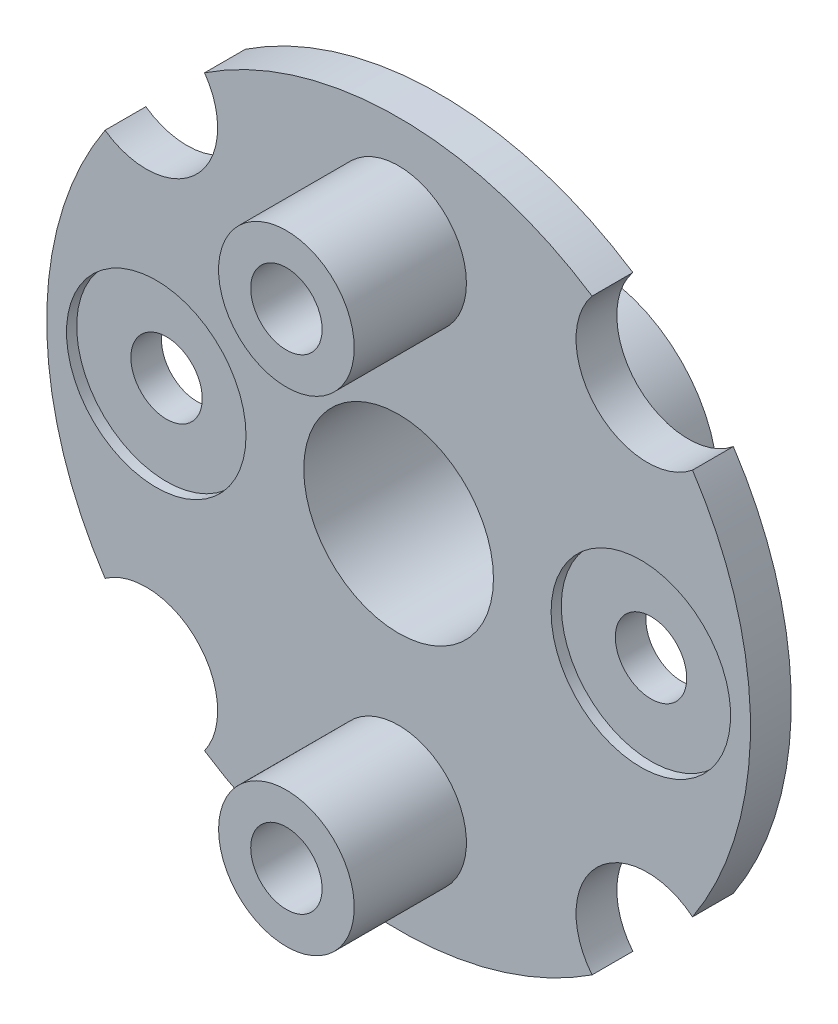
SolidWorks part; units mm, degrees
material "ABS"
ref_plane "Plan de face" through (0, 0, 0) normal (0, 0, 1) x (1, 0, 0)
ref_plane "Plan de dessus" through (0, 0, 0) normal (0, 1, 0) x (1, 0, 0)
ref_plane "Plan de droite" through (0, 0, 0) normal (1, 0, 0) x (0, 0, -1)
sketch "Esquisse1" plane through (0, 0, 0) normal (0, 0, 1) x (1, 0, 0)
  line L0 (0, 0) -> (0, 31.7613) construction
  line L1 (0, 0) -> (40.1621, 0) construction
  line L2 (0, 0) -> (-26.7749, 26.7749) construction
  line L3 (0, 0) -> (27.0466, 27.0466) construction
  arc A0 (-14.3904, 9.5121) -> (-14.3904, -9.5121) centre (0, 0) ccw
  circle A1 centre (0, 0) radius 4.65
  circle A2 centre (0, 11.875) radius 1.75
  circle A3 centre (11.875, 0) radius 1.75
  circle A4 centre (0, 0) radius 11.875 construction
  circle A5 centre (0, -11.875) radius 1.75
  circle A6 centre (-11.875, 0) radius 1.75
  arc A7 (9.4844, 14.4086) -> (14.4086, 9.4844) centre (12.1976, 12.1976) ccw
  arc A8 (-14.3904, 9.5121) -> (-9.5121, 14.3904) centre (-12.3704, 12.3704) ccw
  arc A9 (9.4844, -14.4086) -> (14.4086, -9.4844) centre (12.1976, -12.1976) cw
  arc A10 (-14.3904, -9.5121) -> (-9.5121, -14.3904) centre (-12.3704, -12.3704) cw
  arc A11 (9.4844, 14.4086) -> (-9.5121, 14.3904) centre (0, 0) ccw
  arc A12 (-9.5121, -14.3904) -> (9.4844, -14.4086) centre (0, 0) ccw
  arc A13 (14.4086, -9.4844) -> (12.1976, 12.1976) centre (0, 0) ccw
  dimension "D1" = 34.5
  dimension "D2" = 9.3
  dimension "D3" = 3.5
  dimension "D4" = 23.75
  dimension "D7" = 7
  dimension "D5" = 45
  dimension "D6" = 45
extrude "Boss.-Extru.1" add sketch "Esquisse1" along normal blind 2 contours A9 A13 A7 A11 A8 A0 A10 A12 A6 A1 A2 A3 A5
sketch "Esquisse2" plane through (0, 0, 0) normal (0, 0, -1) x (-1, 0, 0)
  circle A0 centre (0, 0) radius 6.15
  circle A1 centre (0, 0) radius 4.65 construction
  circle A2 centre (0, 0) radius 4.65
extrude "Boss.-Extru.2" add sketch "Esquisse2" along normal blind 7.5
sketch "Esquisse3" plane through (0, 0, 2) normal (0, 0, 1) x (1, 0, 0)
  line L0 (0, 0) -> (30.4064, 0) construction
  circle A0 centre (0, 11.875) radius 3.325
  circle A1 centre (0, 11.875) radius 1.75 construction
  circle A2 centre (0, 11.875) radius 1.75
  circle A3 centre (0, -11.875) radius 1.75
  circle A4 centre (0, -11.875) radius 3.325
  dimension "D1" = 6.65
extrude "Boss.-Extru.3" add sketch "Esquisse3" along normal blind 5.5
sketch "Esquisse4" plane through (0, 0, 2) normal (0, 0, 1) x (1, 0, 0)
  line L0 (0, 0) -> (0, 18.4171) construction
  circle A0 centre (-11.88, 0) radius 4.4
  circle A1 centre (11.875, 0) radius 4.4
  dimension "D1" = 8.8
  dimension "D2" = 11.875
  dimension "D3" = 11.88
extrude "Enlèv. mat.-Extru.1" cut sketch "Esquisse4" against normal blind 0.5
